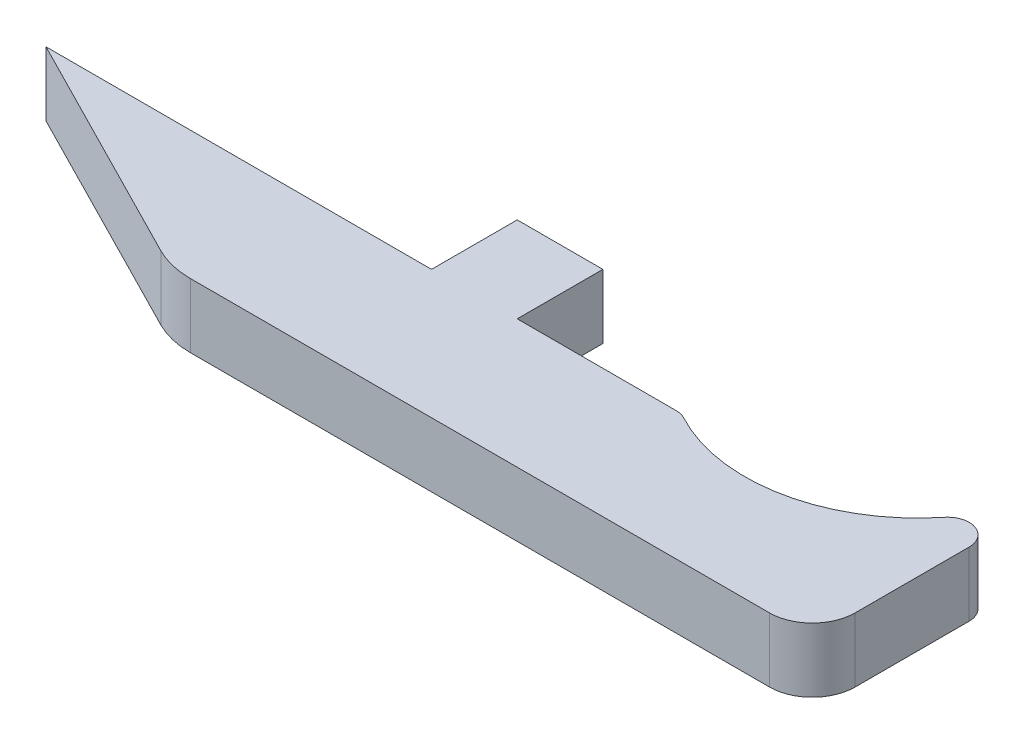
SolidWorks part; units mm, degrees
material "AISI 4130 Steel, annealed at 865C"
ref_plane "X-Y Datum" through (0, 0, 0) normal (0, 0, 1) x (1, 0, 0)
ref_plane "X-Z Datum" through (0, 0, 0) normal (0, 1, 0) x (1, 0, 0)
ref_plane "Y-Z Datum" through (0, 0, 0) normal (1, 0, 0) x (0, 0, -1)
sketch "Sketch1" plane through (0, 0, 0) normal (0, 1, 0) x (1, 0, 0)
  line L0 (59.0181, -15.392) -> (59.0181, 10.008) construction
  line L1 (59.0181, -13.8172) -> (3.2905, -13.8172)
  line L2 (59.0181, -13.8172) -> (59.0181, -2.692)
  line L3 (24.2201, -23.3422) -> (71.8451, -23.3422)
  line L4 (71.8451, -2.692) -> (71.8451, -23.3422)
  line L5 (5.5225, -13.8172) -> (24.2201, -23.3422)
  line L7 (34.0975, -13.8045) -> (2.3475, -13.8045) construction
  line L8 (34.0975, -13.8045) -> (2.3475, -13.8045)
  circle A0 centre (59.0181, -2.692) radius 12.827
  spline S0 degree 3 poles (59.0181, -15.392) (33.6181, -15.392) (33.6181, 10.008) (59.0181, 10.008) (84.4181, 10.008) (84.4181, -15.392) (59.0181, -15.392) (33.6181, -15.392) (33.6181, 10.008) knots -0.5 0 0 0 0.5 0.5 0.5 1 1 1 1.5 1.5 1.5 weights 1 0.333333 0.333333 1 0.333333 0.333333 1 0.333333 0.333333 only from (59.0181, -15.392) to (59.0181, -15.392)
  spline S1 degree 3 poles (59.0181, -15.392) (33.6181, -15.392) (33.6181, 10.008) (59.0181, 10.008) (84.4181, 10.008) (84.4181, -15.392) (59.0181, -15.392) (33.6181, -15.392) (33.6181, 10.008) knots -0.5 0 0 0 0.5 0.5 0.5 1 1 1 1.5 1.5 1.5 weights 1 0.333333 0.333333 1 0.333333 0.333333 1 0.333333 0.333333 only from (59.0181, -15.392) to (59.0181, -15.392) construction
  dimension "D3" = 25.654
  dimension "D5" = 9.525
  dimension "D1" = 55.7276
  dimension "D2" = 11.1252
  dimension "D4" = 3.175
  dimension "D6" = 47.625
extrude "Boss-Extrude1" add sketch "Sketch1" along normal blind 4.7625
fillet "Fillet1" radius 1.5875 2 edges at (52.6336, 2.3813, 13.8172) (71.8451, 2.3813, 2.692)
fillet "Fillet2" radius 6.35 1 edges at (24.2201, 2.3813, 23.3422)
fillet "Fillet3" radius 3.175 1 edges at (71.8451, 2.3813, 23.3422)
sketch "Sketch6" plane through (0, 0, 13.8172) normal (0, 0, -1) x (-1, 0, 0)
  line L0 (-52.2236, 4.7625) -> (-5.5225, 4.7625) construction
  line L1 (-40.4475, 4.7625) -> (-34.0975, 4.7625)
  line L2 (-40.4475, 4.7625) -> (-40.4475, 0)
  line L3 (-40.4475, 0) -> (-34.0975, 0)
  line L4 (-34.0975, 4.7625) -> (-34.0975, 0)
  line L5 (-52.2236, 0) -> (-5.5225, 0) construction
  line L6 (-5.5225, 4.7625) -> (-5.5225, 0) construction
  dimension "D1" = 6.35
  dimension "D2" = 28.575
extrude "Boss-Extrude2" add sketch "Sketch6" along normal blind 6.35
fillet "Fillet4" [suppressed] radius 0.7937
